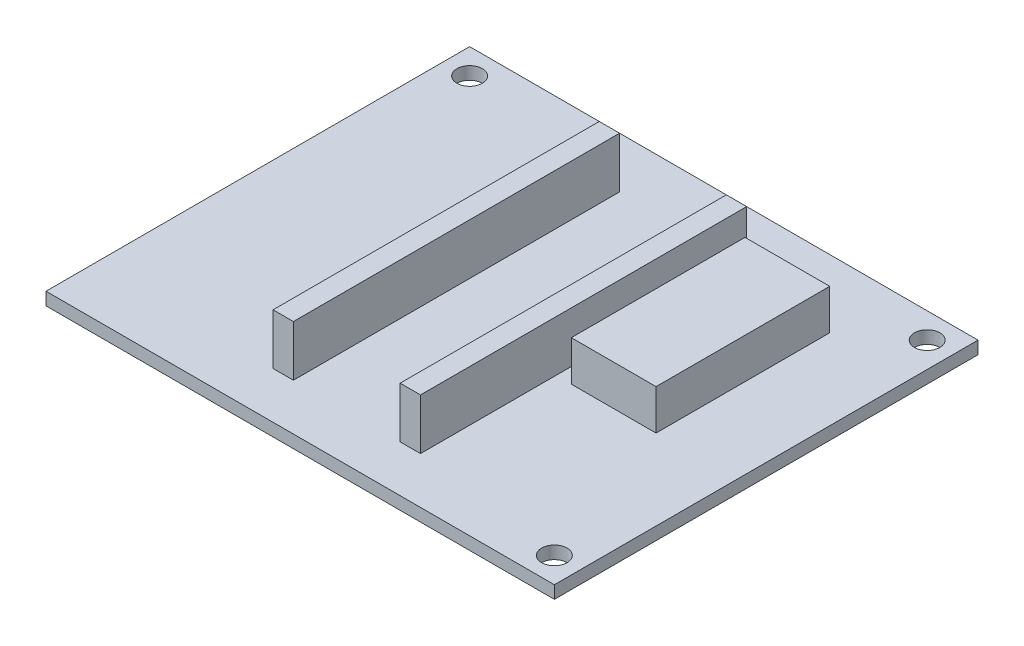
SolidWorks part; units mm, degrees
ref_plane "Front Plane" through (0, 0, 0) normal (0, 0, 1) x (1, 0, 0)
ref_plane "Top Plane" through (0, 0, 0) normal (0, 1, 0) x (1, 0, 0)
ref_plane "Right Plane" through (0, 0, 0) normal (1, 0, 0) x (0, 0, -1)
sketch "Sketch1" plane through (0, 0, 0) normal (0, 1, 0) x (1, 0, 0)
  line L0 (0, -55) -> (0, 55) construction
  line L1 (30, -25) -> (-30, -25)
  line L2 (30, -25) -> (30, 25)
  line L3 (30, 25) -> (-30, 25)
  line L4 (-30, -25) -> (-30, 25)
  line L5 (30, -25) -> (-30, 25) construction
  line L6 (30, 25) -> (-30, -25) construction
  line L7 (-55, 0) -> (55, 0) construction
  circle A0 centre (-27, 22) radius 1.5
  circle A1 centre (27, 22) radius 1.5
  circle A2 centre (27, -22) radius 1.5
  point P0 (0, 0)
  dimension "D3" = 3
  dimension "D1" = 50
  dimension "D2" = 60
  dimension "D4" = 3
  dimension "D5" = 3
extrude "pcb" add sketch "Sketch1" along normal blind 1.5
sketch "Sketch2" plane through (0, 1.5, 0) normal (0, 1, 0) x (1, 0, 0)
  line L0 (-30, 25) -> (-30, -25) construction
  line L1 (-8.7, 19) -> (-6.3, 19)
  line L2 (-8.7, 19) -> (-8.7, -19.5)
  line L3 (-8.7, -19.5) -> (-6.3, -19.5)
  line L4 (-6.3, 19) -> (-6.3, -19.5)
  line L5 (30, 25) -> (-30, 25) construction
  line L6 (6.3, 19) -> (8.7, 19)
  line L7 (6.3, 19) -> (6.3, -19.5)
  line L8 (6.3, -19.5) -> (8.7, -19.5)
  line L9 (8.7, 19) -> (8.7, -19.5)
  dimension "D1" = 21.3
  dimension "D2" = 6
  dimension "D3" = 2.4
  dimension "D4" = 38.5
  dimension "D5" = 36.3
extrude "nano_female_headers" add sketch "Sketch2" along normal blind 6 separate body
sketch "Sketch3" plane through (0, 1.5, 0) normal (0, 1, 0) x (1, 0, 0)
  line L1 (10.5, 17) -> (20.5, 17)
  line L2 (10.5, 17) -> (10.5, -3.5)
  line L3 (10.5, -3.5) -> (20.5, -3.5)
  line L4 (20.5, 17) -> (20.5, -3.5)
  line L5 (10.5, 17) -> (20.5, -3.5) construction
  line L6 (10.5, -3.5) -> (20.5, 17) construction
  line L8 (-30, 25) -> (-30, -25) construction
  line L9 (-30, -25) -> (30, -25) construction
  point P0 (15.5, 6.75)
  dimension "D1" = 10
  dimension "D2" = 45.5
  dimension "D3" = 31.75
  dimension "D4" = 20.5
extrude "dip16_socket" add sketch "Sketch3" along normal blind 4.75 separate body
